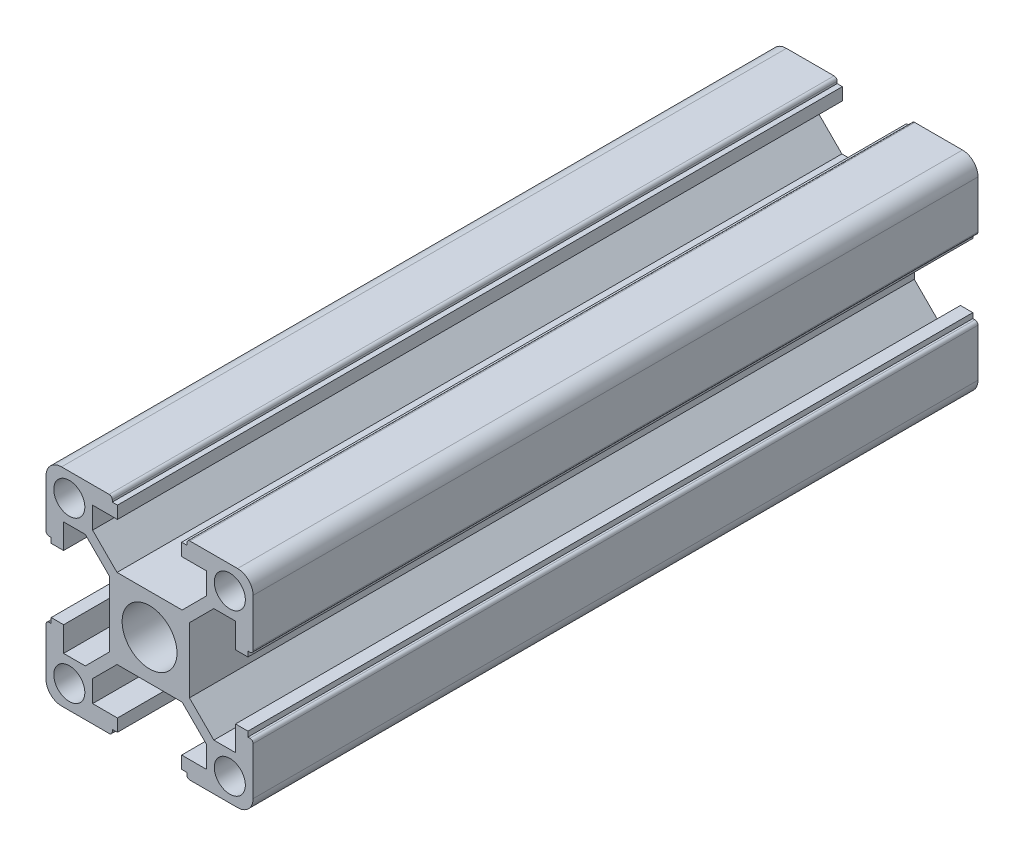
SolidWorks part; units mm, degrees
ref_plane "前视基准面" through (0, 0, 0) normal (0, 0, 1) x (1, 0, 0)
ref_plane "上视基准面" through (0, 0, 0) normal (0, 1, 0) x (1, 0, 0)
ref_plane "右视基准面" through (0, 0, 0) normal (1, 0, 0) x (0, 0, -1)
sketch "草图1" plane through (0, 0, 0) normal (0, 0, 1) x (1, 0, 0)
  line L0 (-7.75, 0) -> (0, 0) construction
  line L1 (7.75, -7.75) -> (-7.75, -7.75) construction
  line L2 (7.75, -7.75) -> (7.75, 7.75) construction
  line L3 (7.75, 7.75) -> (-7.75, 7.75) construction
  line L4 (-7.75, -7.75) -> (-7.75, 7.75) construction
  line L5 (7.75, -7.75) -> (-7.75, 7.75) construction
  line L6 (7.75, 7.75) -> (-7.75, -7.75) construction
  line L7 (0, 0) -> (0, 7.75) construction
  line L8 (3.1429, 3.85) -> (-3.1429, 3.85)
  line L9 (-3.1429, 3.85) -> (-5.5, 6.2071)
  line L10 (-5.5, 6.2071) -> (-5.5, 8.3)
  line L11 (-5.5, 8.3) -> (-3.1, 8.3)
  line L12 (-3.1, 8.3) -> (-3.1, 9.5)
  line L13 (-3.1, 9.5) -> (-3.6, 9.5)
  line L14 (-3.6, 9.5) -> (-3.6, 9.7)
  line L15 (-3.9, 10) -> (-8.5, 10)
  line L16 (-3.85, -3.1429) -> (-3.85, 3.1429)
  line L17 (-3.85, 3.1429) -> (-6.2071, 5.5)
  line L18 (-6.2071, 5.5) -> (-8.3, 5.5)
  line L19 (-8.3, 5.5) -> (-8.3, 3.1)
  line L20 (-9.5, 3.1) -> (-9.5, 3.6)
  line L21 (-8.3, 3.1) -> (-9.5, 3.1)
  line L22 (-9.5, 3.6) -> (-9.7, 3.6)
  line L23 (-10, 3.9) -> (-10, 8.5)
  line L24 (5.5, 8.3) -> (3.1, 8.3)
  line L25 (3.6, 9.5) -> (3.6, 9.7)
  line L26 (3.1, 9.5) -> (3.6, 9.5)
  line L27 (3.1, 8.3) -> (3.1, 9.5)
  line L28 (5.5, 6.2071) -> (5.5, 8.3)
  line L29 (3.1429, 3.85) -> (5.5, 6.2071)
  line L30 (3.85, -3.1429) -> (3.85, 3.1429)
  line L31 (3.85, 3.1429) -> (6.2071, 5.5)
  line L32 (9.5, 3.6) -> (9.7, 3.6)
  line L33 (8.3, 3.1) -> (9.5, 3.1)
  line L34 (9.5, 3.1) -> (9.5, 3.6)
  line L35 (8.3, 5.5) -> (8.3, 3.1)
  line L36 (6.2071, 5.5) -> (8.3, 5.5)
  line L37 (10, 3.9) -> (10, 8.5)
  line L38 (3.9, 10) -> (8.5, 10)
  line L39 (-9.5, -3.6) -> (-9.7, -3.6)
  line L40 (-8.3, -3.1) -> (-9.5, -3.1)
  line L41 (-9.5, -3.1) -> (-9.5, -3.6)
  line L42 (-8.3, -5.5) -> (-8.3, -3.1)
  line L43 (-6.2071, -5.5) -> (-8.3, -5.5)
  line L44 (-3.85, -3.1429) -> (-6.2071, -5.5)
  line L45 (-3.1429, -3.85) -> (-5.5, -6.2071)
  line L46 (-5.5, -6.2071) -> (-5.5, -8.3)
  line L47 (-3.6, -9.5) -> (-3.6, -9.7)
  line L48 (-3.1, -9.5) -> (-3.6, -9.5)
  line L49 (-3.1, -8.3) -> (-3.1, -9.5)
  line L50 (-5.5, -8.3) -> (-3.1, -8.3)
  line L51 (5.5, -6.2071) -> (5.5, -8.3)
  line L52 (3.1, -8.3) -> (3.1, -9.5)
  line L53 (3.1, -9.5) -> (3.6, -9.5)
  line L54 (3.6, -9.5) -> (3.6, -9.7)
  line L55 (5.5, -8.3) -> (3.1, -8.3)
  line L56 (3.1429, -3.85) -> (5.5, -6.2071)
  line L57 (3.1429, -3.85) -> (-3.1429, -3.85)
  line L58 (3.85, -3.1429) -> (6.2071, -5.5)
  line L59 (6.2071, -5.5) -> (8.3, -5.5)
  line L60 (8.3, -5.5) -> (8.3, -3.1)
  line L61 (9.5, -3.1) -> (9.5, -3.6)
  line L62 (8.3, -3.1) -> (9.5, -3.1)
  line L63 (9.5, -3.6) -> (9.7, -3.6)
  line L64 (3.9, -10) -> (8.5, -10)
  line L65 (10, -3.9) -> (10, -8.5)
  line L66 (-10, -3.9) -> (-10, -8.5)
  line L67 (-3.9, -10) -> (-8.5, -10)
  circle A0 centre (0, 0) radius 2.65
  circle A1 centre (-7.75, 7.75) radius 1.5
  circle A2 centre (7.75, 7.75) radius 1.5
  circle A3 centre (7.75, -7.75) radius 1.5
  circle A4 centre (-7.75, -7.75) radius 1.5
  arc A5 (-10, -8.5) -> (-8.5, -10) centre (-8.5, -8.5) ccw
  arc A6 (8.5, -10) -> (10, -8.5) centre (8.5, -8.5) ccw
  arc A7 (10, 8.5) -> (8.5, 10) centre (8.5, 8.5) ccw
  arc A8 (-8.5, 10) -> (-10, 8.5) centre (-8.5, 8.5) ccw
  arc A9 (3.6, -9.7) -> (3.9, -10) centre (3.9, -9.7) ccw
  arc A10 (-3.6, -9.7) -> (-3.9, -10) centre (-3.9, -9.7) cw
  arc A11 (-9.7, -3.6) -> (-10, -3.9) centre (-9.7, -3.9) ccw
  arc A12 (9.7, -3.6) -> (10, -3.9) centre (9.7, -3.9) cw
  arc A13 (9.7, 3.6) -> (10, 3.9) centre (9.7, 3.9) ccw
  arc A14 (-9.7, 3.6) -> (-10, 3.9) centre (-9.7, 3.9) cw
  arc A15 (3.6, 9.7) -> (3.9, 10) centre (3.9, 9.7) cw
  arc A16 (-3.6, 9.7) -> (-3.9, 10) centre (-3.9, 9.7) ccw
  point P46 (0, 3.85)
  point P56 (-3.85, 0)
  point P78 (3.85, 0)
  point P87 (-10, -10)
  point P90 (10, -10)
  point P93 (10, 10)
  point P96 (-10, 10)
  point P99 (3.6, -10)
  point P102 (-3.6, -10)
  point P105 (-10, -3.6)
  point P108 (10, -3.6)
  point P111 (10, 3.6)
  point P114 (-10, 3.6)
  point P117 (3.6, 10)
  point P120 (-3.6, 10)
  dimension "D1" = 5.3
  dimension "D2" = 3
  dimension "D11" = 1.5
  dimension "D12" = 2.25
  dimension "D13" = 0.3
  dimension "D3" = 7.7
  dimension "D4" = 6.2
  dimension "D5" = 1.7
  dimension "D6" = 1.2
  dimension "D7" = 20
  dimension "D8" = 7.2
  dimension "D9" = 11
  dimension "D10" = 1
extrude "凸台-拉伸1" add sketch "草图1" along normal mid plane 70
sketch "草图3" plane through (0, 0, 0) normal (0, 1, 0) x (1, 0, 0)
  line L0 (-3.1429, 35) -> (3.1429, 35) construction
  circle A0 centre (0, -13) radius 2
  dimension "D1" = 48
  dimension "D2" = 4
extrude "切除-拉伸1" cut sketch "草图3" against normal through all both and the other way through all
sketch "草图4" plane through (0, -3.85, 0) normal (0, -1, 0) x (1, 0, 0)
  circle A0 centre (0, 13) radius 4.25
  dimension "D1" = 8.5
extrude "切除-拉伸2" cut sketch "草图4" along normal through all contours A0
sketch "草图5" plane through (0, 0, 0) normal (1, 0, 0) x (0, 0, -1)
  line L0 (35, 3.1429) -> (35, -3.1429) construction
  circle A0 centre (25, 0) radius 2
  dimension "D1" = 4
  dimension "D2" = 10
extrude "切除-拉伸3" cut sketch "草图5" against normal through all both and the other way through all
sketch "草图6" plane through (-3.85, 0, 0) normal (-1, 0, 0) x (0, 0, 1)
  circle A0 centre (-25, 0) radius 4.25
  dimension "D1" = 8.5
extrude "切除-拉伸4" cut sketch "草图6" along normal through all
